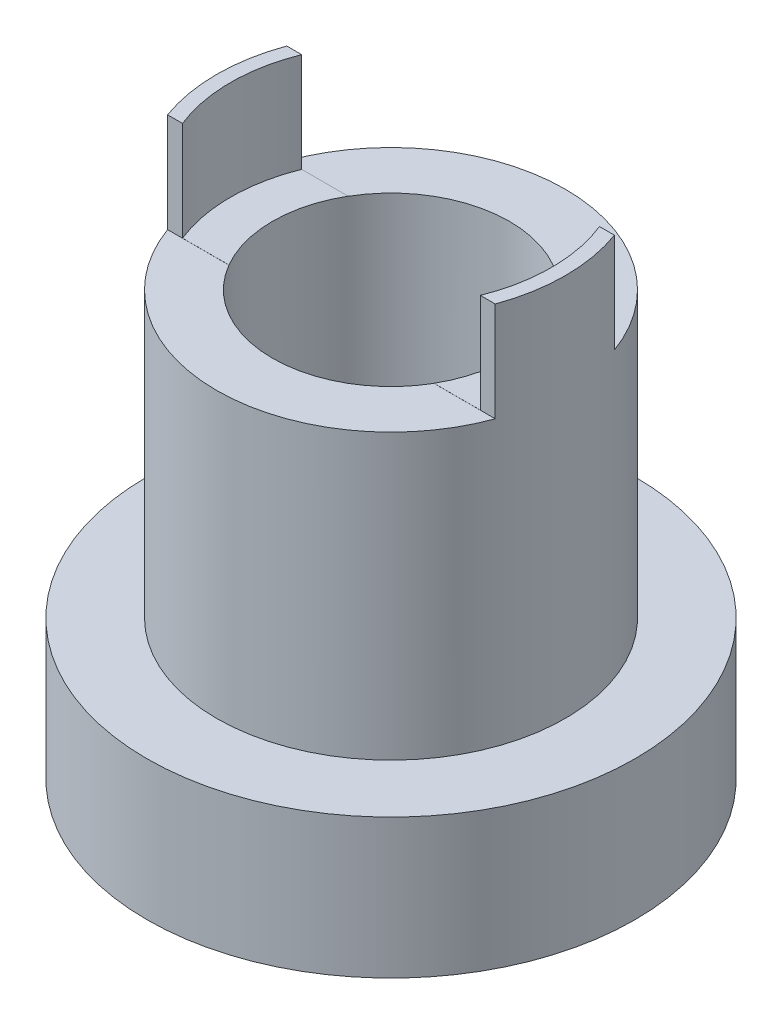
SolidWorks part; units mm, degrees
ref_plane "前视基准面" through (0, 0, 0) normal (0, 0, 1) x (1, 0, 0)
ref_plane "上视基准面" through (0, 0, 0) normal (0, 1, 0) x (1, 0, 0)
ref_plane "右视基准面" through (0, 0, 0) normal (1, 0, 0) x (0, 0, -1)
sketch "草图1" plane through (0, 0, 0) normal (0, 1, 0) x (1, 0, 0)
  circle A0 centre (0, 0) radius 7
  dimension "D1" = 14
extrude "凸台-拉伸1" add sketch "草图1" along normal blind 4
sketch "草图2" plane through (0, 0, 0) normal (0, -1, 0) x (1, 0, 0)
  line L1 (-5.4001, 5.9024) -> (5.4001, 5.9024) construction
  line L2 (-5.4001, 5.9024) -> (-5.4001, -5.9024) construction
  line L3 (-5.4001, -5.9024) -> (5.4001, -5.9024) construction
  line L4 (5.4001, 5.9024) -> (5.4001, -5.9024) construction
  line L5 (0, -5.9024) -> (0, 5.9024) construction
  line L6 (-5.4001, 0) -> (5.4001, 0) construction
  point P0 (0, 0)
  dimension "D1" = 16
  dimension "D2" = 16
sketch "草图5" plane through (0, 4, 0) normal (0, 1, 0) x (1, 0, 0)
  circle A0 centre (0, 0) radius 5
extrude "凸台-拉伸2" add sketch "草图5" along normal blind 11
sketch "草图6" plane through (0, 15, 0) normal (0, 1, 0) x (1, 0, 0)
  circle A0 centre (0, 0) radius 3.5 construction
hole_wizard "M8 螺纹孔1" positions "3D草图1" profile "草图7" tap size "M8" standard "GB" end condition through all
sketch3d "3D草图1"
  point P0 (0, 0, 0)
  point P3 (0, 0, 0)
  point P5 (0, 15, 0)
sketch "草图7" plane through (0, 15, 0) normal (1, 0, 0) x (0, 0, 1)
  line L0 (0, 0) -> (0, 15)
  line L1 (0, 15) -> (3.4, 15)
  line L2 (3.4, 15) -> (3.4, 0)
  line L5 (3.4, 0) -> (0, 0)
  line L11 (0, -6.35) -> (0, 107.95) construction
  dimension "通孔螺纹孔钻头直径" = 6.8
  dimension "通孔螺纹孔钻头深度" = 15
cosmetic thread "孔螺蚊线1" parameters "D2"=8
cosmetic thread "孔螺蚊线2" parameters "D2"=8
cosmetic thread "孔螺蚊线4" parameters "D2"=8
sketch3d "3D草图2"
  point P0 (4.998, 11.2809, 0.1427)
ref_plane "基准面1" through (4.998, 0, 0) normal (1, 0, 0) x (0, 0, -1)
sketch "草图11" plane through (4.998, 0, 0) normal (1, 0, 0) x (0, 0, -1)
  line L0 (0, 15) -> (0, 13.5975) construction
  line L2 (3.4, 15) -> (-3.4, 15) construction
  line L4 (-1.7089, 15.0475) -> (1.7089, 15.0475) construction
  line L5 (-1.7089, 15.0475) -> (-1.7089, 12.1475) construction
  line L6 (-1.7089, 12.1475) -> (1.7089, 12.1475) construction
  line L7 (1.7089, 15.0475) -> (1.7089, 12.1475) construction
  line L8 (0, 12.1475) -> (0, 15.0475) construction
  line L9 (-1.7089, 13.5975) -> (1.7089, 13.5975) construction
  line L10 (1.7089, 15.0475) -> (7.6008, 15.0475)
  line L11 (1.7089, 15.0475) -> (1.7089, 12.1475)
  line L12 (1.7089, 12.1475) -> (7.6008, 12.1475)
  line L13 (7.6008, 15.0475) -> (7.6008, 12.1475)
  line L14 (-1.7089, 12.1475) -> (-6.0121, 12.1475)
  line L15 (-1.7089, 12.1475) -> (-1.7089, 15.0475)
  line L16 (-1.7089, 15.0475) -> (-6.0121, 15.0475)
  line L17 (-6.0121, 12.1475) -> (-6.0121, 15.0475)
  dimension "D1" = 2.9
extrude "切除-拉伸4" cut sketch "草图11" against normal through all and the other way through all
sketch "草图12" plane through (0, 15, 0) normal (0, 1, 0) x (1, 0, 0)
  circle A0 centre (0, 0) radius 4.6
extrude "切除-拉伸5" cut sketch "草图12" against normal blind 2.85
